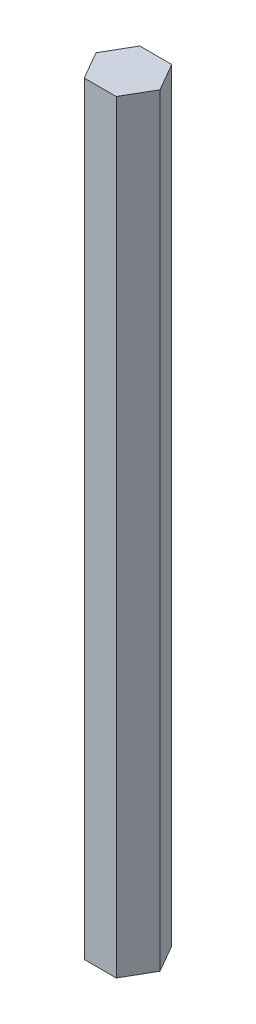
SolidWorks part; units mm, degrees
ref_plane "Front Plane" through (0, 0, 0) normal (0, 0, 1) x (1, 0, 0)
ref_plane "Top Plane" through (0, 0, 0) normal (0, 1, 0) x (1, 0, 0)
ref_plane "Right Plane" through (0, 0, 0) normal (1, 0, 0) x (0, 0, -1)
sketch "Sketch1" plane through (0, 0, 0) normal (0, 1, 0) x (1, 0, 0)
  line L1 (2.0975, 3.633) -> (-2.0975, 3.633)
  line L2 (-2.0975, 3.633) -> (-4.195, 0)
  line L3 (-4.195, 0) -> (-2.0975, -3.633)
  line L4 (-2.0975, -3.633) -> (2.0975, -3.633)
  line L5 (2.0975, -3.633) -> (4.195, 0)
  line L6 (4.195, 0) -> (2.0975, 3.633)
  circle A0 centre (0, 0) radius 3.633 construction
  dimension "D1" = 8.39
extrude "Boss-Extrude1" add sketch "Sketch1" against normal blind 100
